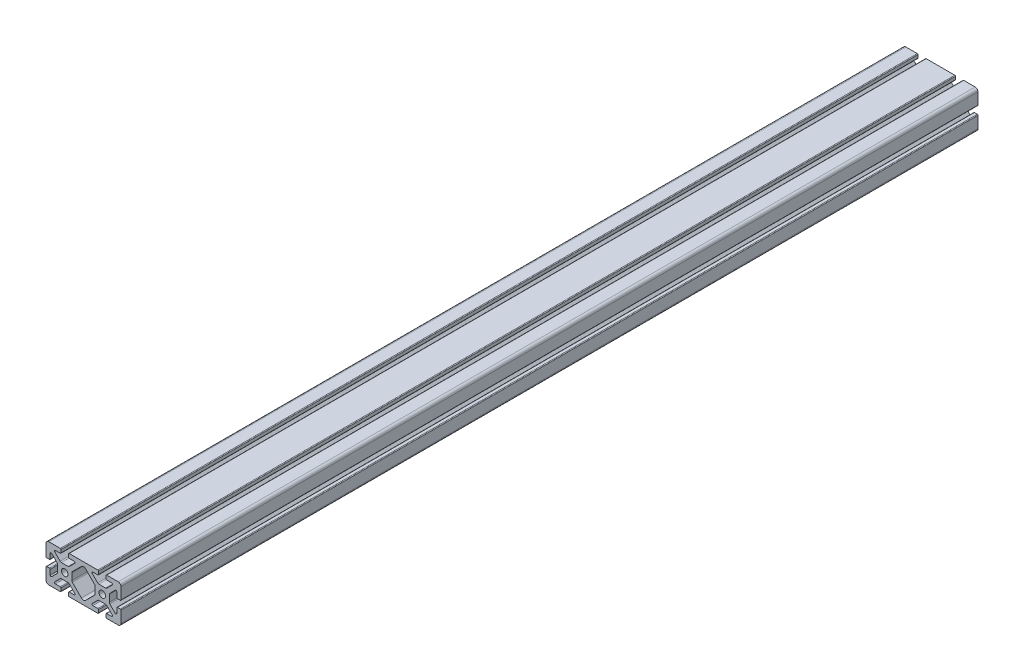
SolidWorks part; units mm, degrees
ref_plane "Front Plane" through (0, 0, 0) normal (0, 0, 1) x (1, 0, 0)
ref_plane "Top Plane" through (0, 0, 0) normal (0, 1, 0) x (1, 0, 0)
ref_plane "Right Plane" through (0, 0, 0) normal (1, 0, 0) x (0, 0, -1)
sketch "Sketch1" plane through (0, 0, 0) normal (0, 0, 1) x (1, 0, 0)
  line L0 (-40, 17) -> (-40, 4.75)
  line L1 (-37, 20) -> (-24.75, 20)
  line L2 (-24, 19.25) -> (-24, 16.25)
  line L3 (-24.75, 15.5) -> (-30.068, 15.5)
  line L4 (-30.727, 13.909) -> (-24.8599, 8.0419)
  line L5 (-33.909, 10.727) -> (-28.0419, 4.8599)
  line L6 (-35.5, 10.068) -> (-35.5, 4.75)
  line L7 (-36.25, 4) -> (-39.25, 4)
  line L8 (-23.5517, 7.5) -> (-16.4483, 7.5)
  line L9 (-27.5, 3.5517) -> (-27.5, -3.5517)
  line L10 (0, 20) -> (-15.25, 20)
  line L11 (-16, 19.25) -> (-16, 16.25)
  line L12 (-15.25, 15.5) -> (-9.932, 15.5)
  line L13 (-12.5, 3.5517) -> (-12.5, -3.5517)
  line L14 (-9.273, 13.909) -> (-15.1401, 8.0419)
  line L15 (-2.25, 14.568) -> (-11.9581, 4.8599)
  line L16 (-36.25, -4) -> (-39.25, -4)
  line L17 (-35.5, -10.068) -> (-35.5, -4.75)
  line L18 (-33.909, -10.727) -> (-28.0419, -4.8599)
  line L19 (-30.727, -13.909) -> (-24.8599, -8.0419)
  line L20 (-24.75, -15.5) -> (-30.068, -15.5)
  line L21 (-24, -19.25) -> (-24, -16.25)
  line L22 (-37, -20) -> (-24.75, -20)
  line L23 (-40, -17) -> (-40, -4.75)
  line L24 (0, -20) -> (-15.25, -20)
  line L25 (-16, -19.25) -> (-16, -16.25)
  line L26 (-15.25, -15.5) -> (-9.932, -15.5)
  line L27 (-9.273, -13.909) -> (-15.1401, -8.0419)
  line L28 (-2.25, -14.568) -> (-11.9581, -4.8599)
  line L29 (-23.5517, -7.5) -> (-16.4483, -7.5)
  line L58 (0, 20) -> (0, -20) construction
  line L59 (-12.5, 0) -> (0, 0) construction
  line L60 (0, 15.5) -> (15.25, 15.5) construction
  line L61 (0, -15.5) -> (15.25, -15.5) construction
  line L62 (-24, 17.75) -> (-16, 17.75) construction
  line L63 (-20, 17.75) -> (-20, 0) construction
  line L64 (-37.75, 4) -> (-37.75, -4) construction
  circle A0 centre (-20, 0) radius 3.5
  arc A1 (-40, 17) -> (-37, 20) centre (-37, 17) cw
  arc A2 (-33.909, 10.727) -> (-35.5, 10.068) centre (-34.568, 10.068) ccw
  arc A3 (-30.068, 15.5) -> (-30.727, 13.909) centre (-30.068, 14.568) ccw
  arc A4 (-24.75, 20) -> (-24, 19.25) centre (-24.75, 19.25) cw
  arc A5 (-40, 4.75) -> (-39.25, 4) centre (-39.25, 4.75) ccw
  arc A6 (-35.5, 4.75) -> (-36.25, 4) centre (-36.25, 4.75) cw
  arc A7 (-24, 16.25) -> (-24.75, 15.5) centre (-24.75, 16.25) cw
  arc A8 (-23.5517, 7.5) -> (-24.8599, 8.0419) centre (-23.5517, 9.35) cw
  arc A9 (-27.5, 3.5517) -> (-28.0419, 4.8599) centre (-29.35, 3.5517) ccw
  arc A10 (0, 15.5) -> (-2.25, 14.568) centre (0, 12.318) ccw
  arc A11 (-2.25, -14.568) -> (0, -15.5) centre (0, -12.318) ccw
  arc A12 (-15.25, 20) -> (-16, 19.25) centre (-15.25, 19.25) ccw
  arc A13 (-16, 16.25) -> (-15.25, 15.5) centre (-15.25, 16.25) ccw
  arc A14 (-16.4483, 7.5) -> (-15.1401, 8.0419) centre (-16.4483, 9.35) ccw
  arc A15 (-12.5, 3.5517) -> (-11.9581, 4.8599) centre (-10.65, 3.5517) cw
  arc A16 (-9.932, 15.5) -> (-9.273, 13.909) centre (-9.932, 14.568) cw
  arc A17 (-27.5, -3.5517) -> (-28.0419, -4.8599) centre (-29.35, -3.5517) cw
  arc A18 (-23.5517, -7.5) -> (-24.8599, -8.0419) centre (-23.5517, -9.35) ccw
  arc A19 (-24, -16.25) -> (-24.75, -15.5) centre (-24.75, -16.25) ccw
  arc A20 (-35.5, -4.75) -> (-36.25, -4) centre (-36.25, -4.75) ccw
  arc A21 (-40, -4.75) -> (-39.25, -4) centre (-39.25, -4.75) cw
  arc A22 (-24.75, -20) -> (-24, -19.25) centre (-24.75, -19.25) ccw
  arc A23 (-30.068, -15.5) -> (-30.727, -13.909) centre (-30.068, -14.568) cw
  arc A24 (-33.909, -10.727) -> (-35.5, -10.068) centre (-34.568, -10.068) cw
  arc A25 (-40, -17) -> (-37, -20) centre (-37, -17) ccw
  arc A26 (-9.932, -15.5) -> (-9.273, -13.909) centre (-9.932, -14.568) ccw
  arc A27 (-15.25, -20) -> (-16, -19.25) centre (-15.25, -19.25) cw
  arc A28 (-16, -16.25) -> (-15.25, -15.5) centre (-15.25, -16.25) cw
  arc A29 (-16.4483, -7.5) -> (-15.1401, -8.0419) centre (-16.4483, -9.35) cw
  arc A30 (-12.5, -3.5517) -> (-11.9581, -4.8599) centre (-10.65, -3.5517) ccw
  point P36 (-27.5, 0)
  point P98 (-37.75, 0)
  point P103 (-20, 7.5)
  point P105 (-20, -7.5)
  dimension "D7" = 7
  dimension "D9" = 3
  dimension "D17" = 0.75
  dimension "D23" = 1.85
  dimension "Rail Width" = 40
  dimension "Rail Height" = 80
  dimension "D3" = 40
  dimension "D4" = 20
  dimension "D6" = 4.5
  dimension "D8" = 4.5
  dimension "D10" = 4.5
  dimension "D11" = 4.5
  dimension "Slot Width" = 8
  dimension "D13" = 45
  dimension "D14" = 45
  dimension "D15" = 4.5
  dimension "D16" = 8
  dimension "D19" = 8
  dimension "D20" = 7.5
  dimension "D21" = 8
  dimension "D22" = 7.5
  dimension "D5" = 22
  dimension "D18" = 22
sketch "Sketch2" plane through (0, 0, 0) normal (1, 0, 0) x (0, 0, -1)
  line L0 (-457.2, -20) -> (457.2, -20)
  point P2 (-419.1, -20)
  point P3 (419.1, -20)
  dimension "Length" = 914.4
  dimension "D1" = 38.1
  dimension "D2" = 38.1
sketch "Sketch3" plane through (0, 0, 0) normal (0, 0, 1) x (1, 0, 0)
  line L0 (0, 20) -> (-15.25, 20) construction
  line L1 (-16, 19.25) -> (-16, 16.25) construction
  line L2 (-15.25, 15.5) -> (-9.932, 15.5) construction
  line L3 (-9.273, 13.909) -> (-15.1401, 8.0419) construction
  line L4 (-23.5517, 7.5) -> (-16.4483, 7.5) construction
  line L5 (-30.727, 13.909) -> (-24.8599, 8.0419) construction
  line L6 (-24.75, 15.5) -> (-30.068, 15.5) construction
  line L7 (-24, 19.25) -> (-24, 16.25) construction
  line L8 (-37, 20) -> (-24.75, 20) construction
  line L9 (-40, 17) -> (-40, 4.75) construction
  line L10 (-36.25, 4) -> (-39.25, 4) construction
  line L11 (-35.5, 10.068) -> (-35.5, 4.75) construction
  line L12 (-33.909, 10.727) -> (-28.0419, 4.8599) construction
  line L13 (-27.5, 3.5517) -> (-27.5, -3.5517) construction
  line L14 (-33.909, -10.727) -> (-28.0419, -4.8599) construction
  line L15 (-35.5, -10.068) -> (-35.5, -4.75) construction
  line L16 (-36.25, -4) -> (-39.25, -4) construction
  line L17 (-40, -17) -> (-40, -4.75) construction
  line L18 (-37, -20) -> (-24.75, -20) construction
  line L19 (-24, -19.25) -> (-24, -16.25) construction
  line L20 (-24.75, -15.5) -> (-30.068, -15.5) construction
  line L21 (-30.727, -13.909) -> (-24.8599, -8.0419) construction
  line L22 (-23.5517, -7.5) -> (-16.4483, -7.5) construction
  line L23 (-9.273, -13.909) -> (-15.1401, -8.0419) construction
  line L24 (-15.25, -15.5) -> (-9.932, -15.5) construction
  line L25 (-16, -19.25) -> (-16, -16.25) construction
  line L26 (0, -20) -> (-15.25, -20) construction
  line L27 (-2.25, -14.568) -> (-11.9581, -4.8599) construction
  line L28 (-12.5, 3.5517) -> (-12.5, -3.5517) construction
  line L29 (-2.25, 14.568) -> (-11.9581, 4.8599) construction
  line L30 (15.25, 20) -> (-15.25, 20)
  line L31 (-16, 19.25) -> (-16, 16.25)
  line L32 (-15.25, 15.5) -> (-9.932, 15.5)
  line L33 (-9.273, 13.909) -> (-15.1401, 8.0419)
  line L34 (-23.5517, 7.5) -> (-16.4483, 7.5)
  line L35 (-30.727, 13.909) -> (-24.8599, 8.0419)
  line L36 (-24.75, 15.5) -> (-30.068, 15.5)
  line L37 (-24, 19.25) -> (-24, 16.25)
  line L38 (-37, 20) -> (-24.75, 20)
  line L39 (-40, 17) -> (-40, 4.75)
  line L40 (-36.25, 4) -> (-39.25, 4)
  line L41 (-35.5, 10.068) -> (-35.5, 4.75)
  line L42 (-33.909, 10.727) -> (-28.0419, 4.8599)
  line L43 (-27.5, 3.5517) -> (-27.5, -3.5517)
  line L44 (-33.909, -10.727) -> (-28.0419, -4.8599)
  line L45 (-35.5, -10.068) -> (-35.5, -4.75)
  line L46 (-36.25, -4) -> (-39.25, -4)
  line L47 (-40, -17) -> (-40, -4.75)
  line L48 (-37, -20) -> (-24.75, -20)
  line L49 (-24, -19.25) -> (-24, -16.25)
  line L50 (-24.75, -15.5) -> (-30.068, -15.5)
  line L51 (-30.727, -13.909) -> (-24.8599, -8.0419)
  line L52 (-23.5517, -7.5) -> (-16.4483, -7.5)
  line L53 (-9.273, -13.909) -> (-15.1401, -8.0419)
  line L54 (-15.25, -15.5) -> (-9.932, -15.5)
  line L55 (-16, -19.25) -> (-16, -16.25)
  line L56 (15.25, -20) -> (-15.25, -20)
  line L57 (-2.25, -14.568) -> (-11.9581, -4.8599)
  line L58 (-12.5, 3.5517) -> (-12.5, -3.5517)
  line L59 (-2.25, 14.568) -> (-11.9581, 4.8599)
  line L60 (0, 20) -> (0, -20) construction
  line L61 (2.25, 14.568) -> (11.9581, 4.8599)
  line L62 (12.5, 3.5517) -> (12.5, -3.5517)
  line L63 (2.25, -14.568) -> (11.9581, -4.8599)
  line L64 (16, 19.25) -> (16, 16.25)
  line L65 (15.25, 15.5) -> (9.932, 15.5)
  line L66 (9.273, 13.909) -> (15.1401, 8.0419)
  line L67 (23.5517, 7.5) -> (16.4483, 7.5)
  line L68 (30.727, 13.909) -> (24.8599, 8.0419)
  line L69 (24.75, 15.5) -> (30.068, 15.5)
  line L70 (24, 19.25) -> (24, 16.25)
  line L71 (37, 20) -> (24.75, 20)
  line L72 (40, 17) -> (40, 4.75)
  line L73 (36.25, 4) -> (39.25, 4)
  line L74 (35.5, 10.068) -> (35.5, 4.75)
  line L75 (33.909, 10.727) -> (28.0419, 4.8599)
  line L76 (27.5, 3.5517) -> (27.5, -3.5517)
  line L77 (33.909, -10.727) -> (28.0419, -4.8599)
  line L78 (35.5, -10.068) -> (35.5, -4.75)
  line L79 (36.25, -4) -> (39.25, -4)
  line L80 (40, -17) -> (40, -4.75)
  line L81 (37, -20) -> (24.75, -20)
  line L82 (24, -19.25) -> (24, -16.25)
  line L83 (24.75, -15.5) -> (30.068, -15.5)
  line L84 (30.727, -13.909) -> (24.8599, -8.0419)
  line L85 (23.5517, -7.5) -> (16.4483, -7.5)
  line L86 (9.273, -13.909) -> (15.1401, -8.0419)
  line L87 (15.25, -15.5) -> (9.932, -15.5)
  line L88 (16, -19.25) -> (16, -16.25)
  circle A0 centre (-20, 0) radius 3.5 construction
  arc A1 (-15.25, 20) -> (-16, 19.25) centre (-15.25, 19.25) ccw construction
  arc A2 (-16, 16.25) -> (-15.25, 15.5) centre (-15.25, 16.25) ccw construction
  arc A3 (-9.273, 13.909) -> (-9.932, 15.5) centre (-9.932, 14.568) ccw construction
  arc A4 (-16.4483, 7.5) -> (-15.1401, 8.0419) centre (-16.4483, 9.35) ccw construction
  arc A5 (-24.8599, 8.0419) -> (-23.5517, 7.5) centre (-23.5517, 9.35) ccw construction
  arc A6 (-30.068, 15.5) -> (-30.727, 13.909) centre (-30.068, 14.568) ccw construction
  arc A7 (-24.75, 15.5) -> (-24, 16.25) centre (-24.75, 16.25) ccw construction
  arc A8 (-24, 19.25) -> (-24.75, 20) centre (-24.75, 19.25) ccw construction
  arc A9 (-37, 20) -> (-40, 17) centre (-37, 17) ccw construction
  arc A10 (-40, 4.75) -> (-39.25, 4) centre (-39.25, 4.75) ccw construction
  arc A11 (-36.25, 4) -> (-35.5, 4.75) centre (-36.25, 4.75) ccw construction
  arc A12 (-33.909, 10.727) -> (-35.5, 10.068) centre (-34.568, 10.068) ccw construction
  arc A13 (-27.5, 3.5517) -> (-28.0419, 4.8599) centre (-29.35, 3.5517) ccw construction
  arc A14 (-28.0419, -4.8599) -> (-27.5, -3.5517) centre (-29.35, -3.5517) ccw construction
  arc A15 (-35.5, -10.068) -> (-33.909, -10.727) centre (-34.568, -10.068) ccw construction
  arc A16 (-35.5, -4.75) -> (-36.25, -4) centre (-36.25, -4.75) ccw construction
  arc A17 (-39.25, -4) -> (-40, -4.75) centre (-39.25, -4.75) ccw construction
  arc A18 (-40, -17) -> (-37, -20) centre (-37, -17) ccw construction
  arc A19 (-24.75, -20) -> (-24, -19.25) centre (-24.75, -19.25) ccw construction
  arc A20 (-24, -16.25) -> (-24.75, -15.5) centre (-24.75, -16.25) ccw construction
  arc A21 (-30.727, -13.909) -> (-30.068, -15.5) centre (-30.068, -14.568) ccw construction
  arc A22 (-23.5517, -7.5) -> (-24.8599, -8.0419) centre (-23.5517, -9.35) ccw construction
  arc A23 (-15.1401, -8.0419) -> (-16.4483, -7.5) centre (-16.4483, -9.35) ccw construction
  arc A24 (-9.932, -15.5) -> (-9.273, -13.909) centre (-9.932, -14.568) ccw construction
  arc A25 (-15.25, -15.5) -> (-16, -16.25) centre (-15.25, -16.25) ccw construction
  arc A26 (-16, -19.25) -> (-15.25, -20) centre (-15.25, -19.25) ccw construction
  arc A27 (-2.25, -14.568) -> (0, -15.5) centre (0, -12.318) ccw construction
  arc A28 (-12.5, -3.5517) -> (-11.9581, -4.8599) centre (-10.65, -3.5517) ccw construction
  arc A29 (-11.9581, 4.8599) -> (-12.5, 3.5517) centre (-10.65, 3.5517) ccw construction
  arc A30 (0, 15.5) -> (-2.25, 14.568) centre (0, 12.318) ccw construction
  circle A31 centre (-20, 0) radius 3.5
  arc A32 (-15.25, 20) -> (-16, 19.25) centre (-15.25, 19.25) ccw
  arc A33 (-16, 16.25) -> (-15.25, 15.5) centre (-15.25, 16.25) ccw
  arc A34 (-9.273, 13.909) -> (-9.932, 15.5) centre (-9.932, 14.568) ccw
  arc A35 (-16.4483, 7.5) -> (-15.1401, 8.0419) centre (-16.4483, 9.35) ccw
  arc A36 (-24.8599, 8.0419) -> (-23.5517, 7.5) centre (-23.5517, 9.35) ccw
  arc A37 (-30.068, 15.5) -> (-30.727, 13.909) centre (-30.068, 14.568) ccw
  arc A38 (-24.75, 15.5) -> (-24, 16.25) centre (-24.75, 16.25) ccw
  arc A39 (-24, 19.25) -> (-24.75, 20) centre (-24.75, 19.25) ccw
  arc A40 (-37, 20) -> (-40, 17) centre (-37, 17) ccw
  arc A41 (-40, 4.75) -> (-39.25, 4) centre (-39.25, 4.75) ccw
  arc A42 (-36.25, 4) -> (-35.5, 4.75) centre (-36.25, 4.75) ccw
  arc A43 (-33.909, 10.727) -> (-35.5, 10.068) centre (-34.568, 10.068) ccw
  arc A44 (-27.5, 3.5517) -> (-28.0419, 4.8599) centre (-29.35, 3.5517) ccw
  arc A45 (-28.0419, -4.8599) -> (-27.5, -3.5517) centre (-29.35, -3.5517) ccw
  arc A46 (-35.5, -10.068) -> (-33.909, -10.727) centre (-34.568, -10.068) ccw
  arc A47 (-35.5, -4.75) -> (-36.25, -4) centre (-36.25, -4.75) ccw
  arc A48 (-39.25, -4) -> (-40, -4.75) centre (-39.25, -4.75) ccw
  arc A49 (-40, -17) -> (-37, -20) centre (-37, -17) ccw
  arc A50 (-24.75, -20) -> (-24, -19.25) centre (-24.75, -19.25) ccw
  arc A51 (-24, -16.25) -> (-24.75, -15.5) centre (-24.75, -16.25) ccw
  arc A52 (-30.727, -13.909) -> (-30.068, -15.5) centre (-30.068, -14.568) ccw
  arc A53 (-23.5517, -7.5) -> (-24.8599, -8.0419) centre (-23.5517, -9.35) ccw
  arc A54 (-15.1401, -8.0419) -> (-16.4483, -7.5) centre (-16.4483, -9.35) ccw
  arc A55 (-9.932, -15.5) -> (-9.273, -13.909) centre (-9.932, -14.568) ccw
  arc A56 (-15.25, -15.5) -> (-16, -16.25) centre (-15.25, -16.25) ccw
  arc A57 (-16, -19.25) -> (-15.25, -20) centre (-15.25, -19.25) ccw
  arc A58 (-2.25, -14.568) -> (2.25, -14.568) centre (0, -12.318) ccw
  arc A59 (-12.5, -3.5517) -> (-11.9581, -4.8599) centre (-10.65, -3.5517) ccw
  arc A60 (-11.9581, 4.8599) -> (-12.5, 3.5517) centre (-10.65, 3.5517) ccw
  arc A61 (2.25, 14.568) -> (-2.25, 14.568) centre (0, 12.318) ccw
  circle A62 centre (20, 0) radius 3.5
  arc A63 (11.9581, 4.8599) -> (12.5, 3.5517) centre (10.65, 3.5517) cw
  arc A64 (12.5, -3.5517) -> (11.9581, -4.8599) centre (10.65, -3.5517) cw
  arc A65 (15.25, 20) -> (16, 19.25) centre (15.25, 19.25) cw
  arc A66 (16, 16.25) -> (15.25, 15.5) centre (15.25, 16.25) cw
  arc A67 (9.273, 13.909) -> (9.932, 15.5) centre (9.932, 14.568) cw
  arc A68 (16.4483, 7.5) -> (15.1401, 8.0419) centre (16.4483, 9.35) cw
  arc A69 (24.8599, 8.0419) -> (23.5517, 7.5) centre (23.5517, 9.35) cw
  arc A70 (30.068, 15.5) -> (30.727, 13.909) centre (30.068, 14.568) cw
  arc A71 (24.75, 15.5) -> (24, 16.25) centre (24.75, 16.25) cw
  arc A72 (24, 19.25) -> (24.75, 20) centre (24.75, 19.25) cw
  arc A73 (37, 20) -> (40, 17) centre (37, 17) cw
  arc A74 (40, 4.75) -> (39.25, 4) centre (39.25, 4.75) cw
  arc A75 (36.25, 4) -> (35.5, 4.75) centre (36.25, 4.75) cw
  arc A76 (33.909, 10.727) -> (35.5, 10.068) centre (34.568, 10.068) cw
  arc A77 (27.5, 3.5517) -> (28.0419, 4.8599) centre (29.35, 3.5517) cw
  arc A78 (28.0419, -4.8599) -> (27.5, -3.5517) centre (29.35, -3.5517) cw
  arc A79 (35.5, -10.068) -> (33.909, -10.727) centre (34.568, -10.068) cw
  arc A80 (35.5, -4.75) -> (36.25, -4) centre (36.25, -4.75) cw
  arc A81 (39.25, -4) -> (40, -4.75) centre (39.25, -4.75) cw
  arc A82 (40, -17) -> (37, -20) centre (37, -17) cw
  arc A83 (24.75, -20) -> (24, -19.25) centre (24.75, -19.25) cw
  arc A84 (24, -16.25) -> (24.75, -15.5) centre (24.75, -16.25) cw
  arc A85 (30.727, -13.909) -> (30.068, -15.5) centre (30.068, -14.568) cw
  arc A86 (23.5517, -7.5) -> (24.8599, -8.0419) centre (23.5517, -9.35) cw
  arc A87 (15.1401, -8.0419) -> (16.4483, -7.5) centre (16.4483, -9.35) cw
  arc A88 (9.932, -15.5) -> (9.273, -13.909) centre (9.932, -14.568) cw
  arc A89 (15.25, -15.5) -> (16, -16.25) centre (15.25, -16.25) cw
  arc A90 (16, -19.25) -> (15.25, -20) centre (15.25, -19.25) cw
extrude "Boss-Extrude1" add sketch "Sketch3" along normal mid plane 914.4
equation "\"D10@Sketch1\"=\"D8@Sketch1\""
equation "\"D11@Sketch1\"=\"D10@Sketch1\""
equation "\"D15@Sketch1\"=\"D6@Sketch1\""
equation "\"D16@Sketch1\" = \"Slot Width@Sketch1\""
equation "\"D18@Sketch1\"=\"D5@Sketch1\""
equation "\"D1@Boss-Extrude1\"=\"Length@Sketch2\""
equation "\"D2@Sketch2\"=\"D1@Sketch2\""
